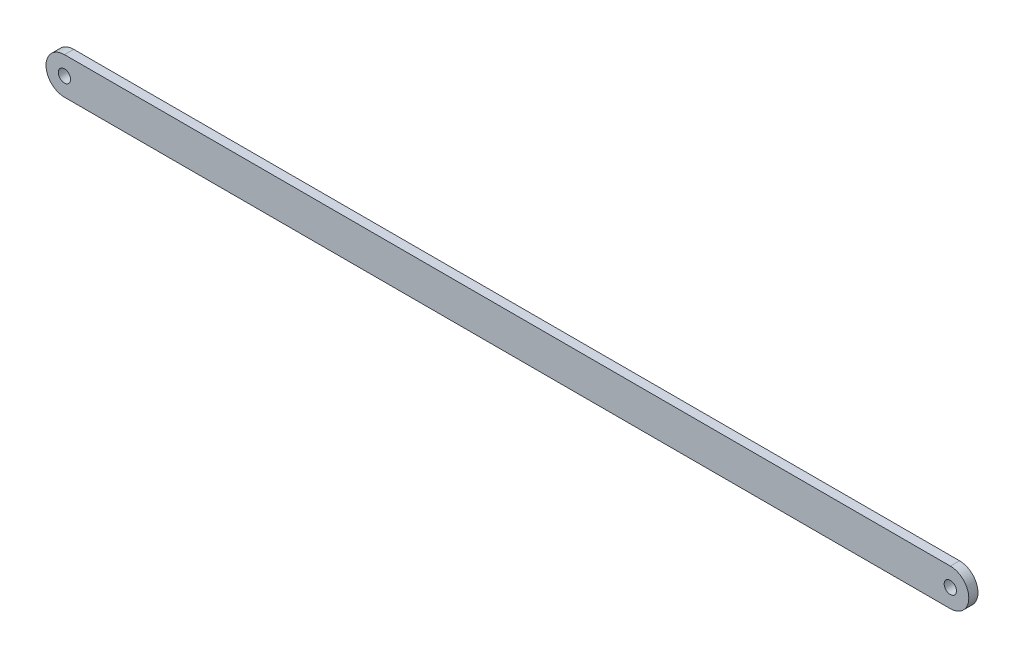
SolidWorks part; units mm, degrees
ref_plane "Front Plane" through (0, 0, 0) normal (0, 0, 1) x (1, 0, 0)
ref_plane "Top Plane" through (0, 0, 0) normal (0, 1, 0) x (1, 0, 0)
ref_plane "Right Plane" through (0, 0, 0) normal (1, 0, 0) x (0, 0, -1)
sketch "Sketch1" plane through (0, 0, 0) normal (0, 0, 1) x (1, 0, 0)
  line L0 (-35.3127, 0) -> (252.6873, 0) construction
  line L1 (-35.3127, 6) -> (252.6873, 6)
  line L2 (-35.3127, -6) -> (252.6873, -6)
  arc A0 (-35.3127, 6) -> (-35.3127, -6) centre (-35.3127, 0) ccw
  arc A1 (252.6873, -6) -> (252.6873, 6) centre (252.6873, 0) ccw
  circle A2 centre (-35.3127, 0) radius 2
  circle A3 centre (252.6873, 0) radius 2
  point P3 (108.6873, 0)
  dimension "D3" = 4
  dimension "D4" = 4
  dimension "D1" = 288
  dimension "D2" = 12
extrude "Boss-Extrude3" add sketch "Sketch1" along normal blind 3
